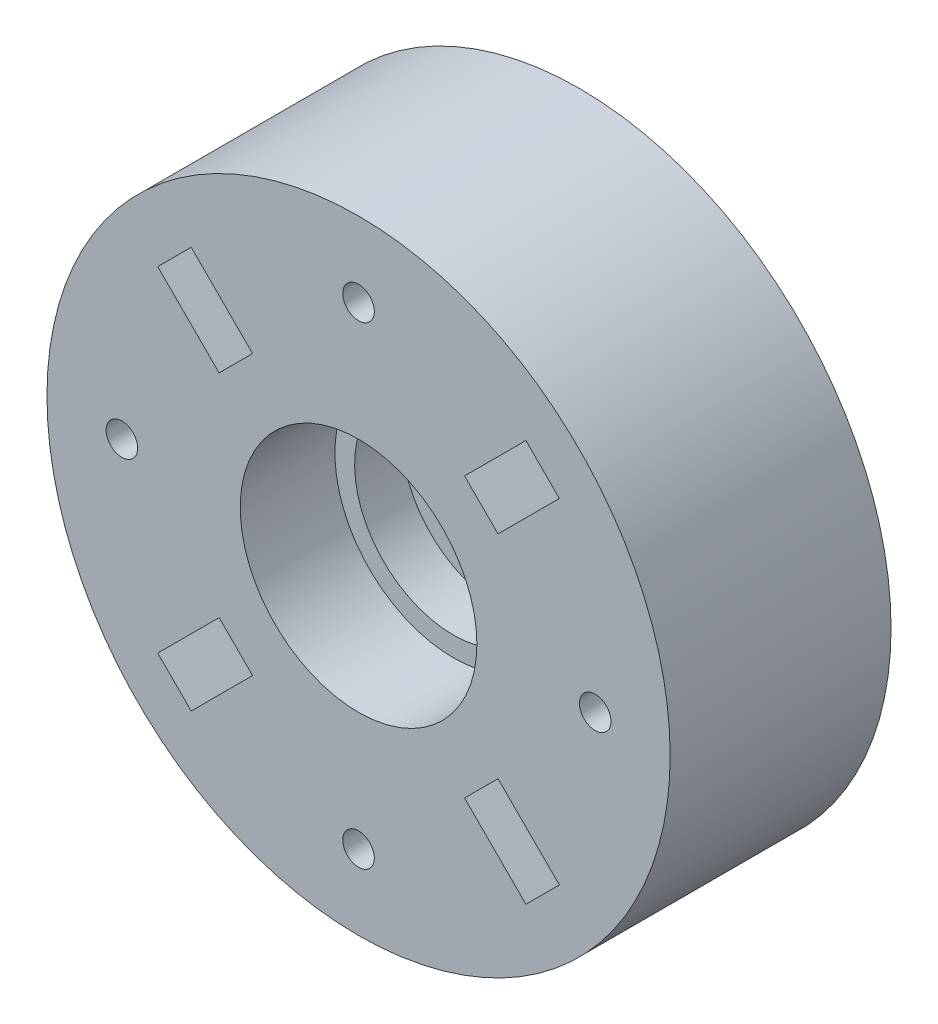
SolidWorks part; units mm, degrees
ref_plane "Alzado" through (0, 0, 0) normal (0, 0, 1) x (1, 0, 0)
ref_plane "Planta" through (0, 0, 0) normal (0, 1, 0) x (1, 0, 0)
ref_plane "Vista lateral" through (0, 0, 0) normal (1, 0, 0) x (0, 0, -1)
sketch "Croquis1" plane through (0, 0, 0) normal (0, 0, 1) x (1, 0, 0)
  line L0 (0, 50.6458) -> (0, -51.1293) construction
  circle A0 centre (0, 0) radius 39.5
  circle A1 centre (0, 0) radius 12.5
  circle A2 centre (0, 30) radius 2
  circle A3 centre (30, 0) radius 2
  circle A4 centre (0, -30) radius 2
  circle A5 centre (-30, 0) radius 2
  point P17 (0, 0)
  dimension "D1" = 79
  dimension "D2" = 25
  dimension "D4" = 4
  dimension "D3" = 30
  dimension "D5" = 4
extrude "Saliente-Extruir1" add sketch "Croquis1" along normal blind 28
sketch "Croquis3" plane through (0, 0, 28) normal (0, 0, 1) x (1, 0, 0)
  line L0 (10.6066, 10.6066) -> (28.2843, 28.2843) construction
  line L1 (0, 0) -> (39.5, 0) construction
  line L2 (17.6777, 13.435) -> (25.4558, 21.2132)
  line L3 (17.6777, 13.435) -> (13.435, 17.6777)
  line L4 (25.4558, 21.2132) -> (21.2132, 25.4558)
  line L5 (13.435, 17.6777) -> (21.2132, 25.4558)
  line L6 (17.6777, 13.435) -> (21.2132, 25.4558) construction
  line L7 (25.4558, 21.2132) -> (13.435, 17.6777) construction
  line L20 (13.435, -17.6777) -> (21.2132, -25.4558)
  line L21 (13.435, -17.6777) -> (17.6777, -13.435)
  line L22 (17.6777, -13.435) -> (25.4558, -21.2132)
  line L23 (21.2132, -25.4558) -> (25.4558, -21.2132)
  line L24 (-17.6777, -13.435) -> (-25.4558, -21.2132)
  line L25 (-17.6777, -13.435) -> (-13.435, -17.6777)
  line L26 (-13.435, -17.6777) -> (-21.2132, -25.4558)
  line L27 (-25.4558, -21.2132) -> (-21.2132, -25.4558)
  line L28 (-13.435, 17.6777) -> (-21.2132, 25.4558)
  line L29 (-13.435, 17.6777) -> (-17.6777, 13.435)
  line L30 (-17.6777, 13.435) -> (-25.4558, 21.2132)
  line L31 (-21.2132, 25.4558) -> (-25.4558, 21.2132)
  circle A0 centre (0, 0) radius 39.5 construction
  circle A1 centre (0, 0) radius 15
  point P8 (19.4454, 19.4454)
  point P27 (0.3536, 0.3536)
  point P30 (0, 0)
  dimension "D9" = 30
  dimension "D1" = 40
  dimension "D2" = 45
  dimension "D3" = 3
  dimension "D4" = 3
  dimension "D5" = 11
  dimension "D6" = 27.5
  dimension "D7" = 6
  dimension "D8" = 4
extrude "Cortar-Extruir1" cut sketch "Croquis3" against normal blind 12
sketch "Croquis5" plane through (0, 0, 0) normal (0, 0, -1) x (-1, 0, 0)
  circle A0 centre (0, 0) radius 16.8579
  dimension "D1" = 33.7158
extrude "Saliente-Extruir2" add sketch "Croquis5" against normal blind 10
sketch "Croquis4" plane through (0, 0, 0) normal (0, 0, -1) x (-1, 0, 0)
  line L0 (30, -3.5) -> (33.0311, -1.75)
  line L1 (3.5, 30) -> (1.75, 33.0311)
  line L2 (1.75, 33.0311) -> (-1.75, 33.0311)
  line L3 (-1.75, 33.0311) -> (-3.5, 30)
  line L4 (-3.5, 30) -> (-1.75, 26.9689)
  line L5 (-1.75, 26.9689) -> (1.75, 26.9689)
  line L6 (1.75, 26.9689) -> (3.5, 30)
  line L7 (33.0311, -1.75) -> (33.0311, 1.75)
  line L8 (33.0311, 1.75) -> (30, 3.5)
  line L9 (30, 3.5) -> (26.9689, 1.75)
  line L10 (26.9689, 1.75) -> (26.9689, -1.75)
  line L11 (26.9689, -1.75) -> (30, -3.5)
  line L12 (-3.5, -30) -> (-1.75, -33.0311)
  line L13 (-1.75, -33.0311) -> (1.75, -33.0311)
  line L14 (1.75, -33.0311) -> (3.5, -30)
  line L15 (3.5, -30) -> (1.75, -26.9689)
  line L16 (1.75, -26.9689) -> (-1.75, -26.9689)
  line L17 (-1.75, -26.9689) -> (-3.5, -30)
  line L18 (-30, 3.5) -> (-33.0311, 1.75)
  line L19 (-33.0311, 1.75) -> (-33.0311, -1.75)
  line L20 (-33.0311, -1.75) -> (-30, -3.5)
  line L21 (-30, -3.5) -> (-26.9689, -1.75)
  line L22 (-26.9689, -1.75) -> (-26.9689, 1.75)
  line L23 (-26.9689, 1.75) -> (-30, 3.5)
  line L24 (0, 0) -> (28.2843, 28.2843) construction
  line L25 (0, 0) -> (39.5, 0) construction
  line L26 (0.3536, -13.7886) -> (29.3449, 15.2028)
  line L27 (0.3536, -13.7886) -> (-13.7886, 0.3536)
  line L28 (29.3449, 15.2028) -> (15.2028, 29.3449)
  line L29 (-13.7886, 0.3536) -> (15.2028, 29.3449)
  line L30 (0.3536, -13.7886) -> (15.2028, 29.3449) construction
  line L31 (29.3449, 15.2028) -> (-13.7886, 0.3536) construction
  line L32 (25.1023, 25.1023) -> (18.7383, 31.4663) construction
  line L33 (25.1023, 25.1023) -> (28.9736, 21.231) construction
  line L34 (0, 0) -> (-15.8104, -15.8104) construction
  line L35 (-9.5459, -9.5459) -> (-4.5375, -14.5544) construction
  line L36 (-9.5459, -9.5459) -> (-14.3054, -4.7865) construction
  line L37 (21.9203, 28.2843) -> (-17.5609, -11.1969) construction
  line L38 (28.2843, 21.9203) -> (-9.2053, -15.5692) construction
  circle A0 centre (0, 30) radius 3.5 construction
  circle A1 centre (0, 0) radius 39.5 construction
  circle A3 centre (-12.7279, -6.364) radius 1.75
  circle A4 centre (-6.364, -12.7279) radius 1.75
  circle A5 centre (21.9203, 28.2843) radius 1.75
  circle A6 centre (28.2843, 21.9203) radius 1.75
  point P30 (0, 0)
  point P36 (7.7782, 7.7782)
  dimension "D11" = 3.5
  dimension "D12" = 3.5
  dimension "D13" = 3.5
  dimension "D14" = 3.5
  dimension "D1" = 4
  dimension "D2" = 40
  dimension "D3" = 45
  dimension "D4" = 20
  dimension "D5" = 10
  dimension "D6" = 9.5
  dimension "D7" = 4.5
  dimension "D8" = 4.5
  dimension "D9" = 4
  dimension "D10" = 4
  dimension "D15" = 41
extrude "Cortar-Extruir2" cut sketch "Croquis4" against normal blind 10
